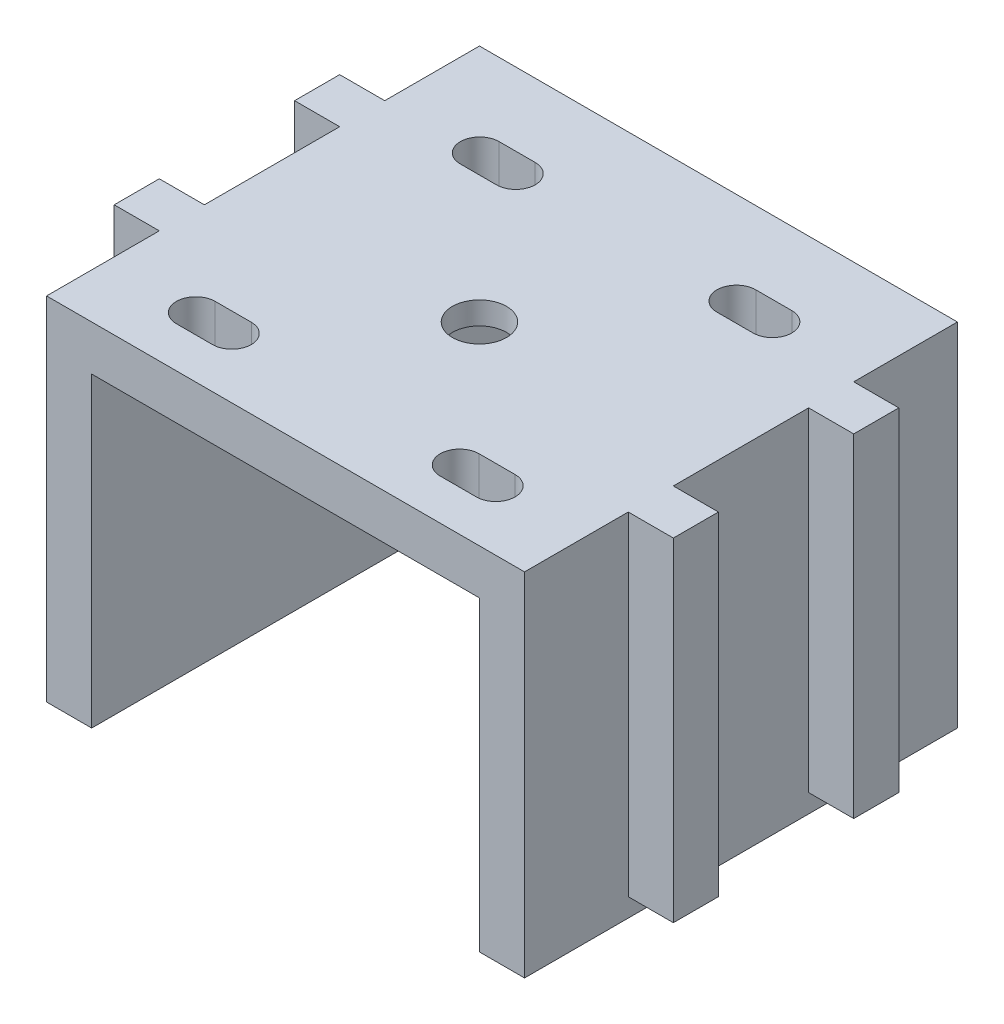
SolidWorks part; units mm, degrees
ref_plane "Front Plane" through (0, 0, 0) normal (1, 0, 0) x (0, 1, 0)
ref_plane "Top Plane" through (0, 0, 0) normal (0, 0, 1) x (0, 1, 0)
ref_plane "Right Plane" through (0, 0, 0) normal (0, 1, 0) x (-1, 0, 0)
sketch "Sketch1" plane through (0, 0, 0) normal (0, 0, 1) x (0, 1, 0)
  line L0 (3.6144, 8.8715) -> (-15.8856, 8.8715)
  line L2 (3.6144, 8.8715) -> (3.6144, -34.1285)
  line L5 (-15.8856, 8.8715) -> (-15.8856, 13.8715)
  line L6 (-15.8856, 13.8715) -> (23.1144, 13.8715)
  line L7 (23.1144, 13.8715) -> (23.1144, -39.1285)
  line L8 (23.1144, -39.1285) -> (-15.8856, -39.1285)
  line L9 (-15.8856, -39.1285) -> (-15.8856, -34.1285)
  line L10 (-15.8856, -34.1285) -> (3.6144, -34.1285)
  dimension "D1" = 39
  dimension "D3" = 19.5
  dimension "D5" = 53
  dimension "D6" = 5
extrude "Boss-Extrude4" add sketch "Sketch1" along normal blind 48
sketch "Sketch2" plane through (0, 0, 48) normal (0, 0, 1) x (1, 0, 0)
  line L0 (39.1285, 23.1144) -> (-13.8715, 23.1144) construction
  line L1 (-8.8715, 18.1144) -> (34.1285, 18.1144)
  line L2 (-8.8715, 18.1144) -> (-8.8715, -24.8856)
  line L3 (-8.8715, -24.8856) -> (34.1285, -24.8856)
  line L4 (34.1285, 18.1144) -> (34.1285, -24.8856)
  line L5 (-13.8715, 23.1144) -> (-13.8715, -15.8856) construction
  dimension "D1" = 43
  dimension "D2" = 43
  dimension "D3" = 5
  dimension "D4" = 5
extrude "Cut-Extrude2" cut sketch "Sketch2" against normal blind 43 contours L2 L3 L4 L1
sketch "Sketch5" plane through (0, 18.1144, 0) normal (0, -1, 0) x (1, 0, 0)
  line L0 (34.1285, 5) -> (34.1285, 48) construction
  line L1 (-8.8715, 5) -> (34.1285, 5) construction
  circle A0 centre (12.6285, 26.5) radius 11.15
  dimension "D1" = 22.3
  dimension "D2" = 21.5
  dimension "D3" = 21.5
extrude "Cut-Extrude3" cut sketch "Sketch5" against normal blind 2.5
sketch "Sketch7" plane through (0, 20.6144, 0) normal (0, -1, 0) x (1, 0, 0)
  circle A0 centre (12.6285, 26.5) radius 3
  circle A1 centre (12.6285, 26.5) radius 11.15 construction
  circle A2 centre (12.6285, 26.5) radius 11.15 construction
  dimension "D1" = 6
  dimension "D2" = 0
  dimension "D3" = 0
extrude "Cut-Extrude4" cut sketch "Sketch7" against normal blind 2.5
sketch "Sketch8" plane through (0, 18.1144, 0) normal (0, -1, 0) x (1, 0, 0)
  line L0 (-4, 41.3244) -> (0, 41.3244) construction
  line L1 (-4, 43.4744) -> (0, 43.4744)
  line L2 (-4, 39.1744) -> (0, 39.1744)
  line L3 (-3.5994, 10.2404) -> (0.4006, 10.2404) construction
  line L4 (28.8564, 10.2404) -> (24.8564, 10.2404) construction
  line L5 (28.8564, 12.3904) -> (24.8564, 12.3904)
  line L6 (12.6285, 48) -> (12.6285, 0) construction
  line L7 (-8.8715, 48) -> (34.1285, 48) construction
  line L8 (-8.8715, 0) -> (34.1285, 0) construction
  line L9 (29.2571, 41.3244) -> (25.2571, 41.3244) construction
  line L10 (29.2571, 43.4744) -> (25.2571, 43.4744)
  line L11 (29.2571, 39.1744) -> (25.2571, 39.1744)
  line L12 (28.8564, 8.0904) -> (24.8564, 8.0904)
  line L13 (-3.5994, 12.3904) -> (0.4006, 12.3904)
  line L14 (-3.5994, 8.0904) -> (0.4006, 8.0904)
  arc A4 (-4, 43.4744) -> (-4, 39.1744) centre (-4, 41.3244) ccw
  arc A5 (0, 39.1744) -> (0, 43.4744) centre (0, 41.3244) ccw
  arc A6 (29.2571, 43.4744) -> (29.2571, 39.1744) centre (29.2571, 41.3244) cw
  arc A7 (25.2571, 39.1744) -> (25.2571, 43.4744) centre (25.2571, 41.3244) cw
  arc A8 (-3.5994, 12.3904) -> (-3.5994, 8.0904) centre (-3.5994, 10.2404) ccw
  arc A9 (0.4006, 8.0904) -> (0.4006, 12.3904) centre (0.4006, 10.2404) ccw
  arc A10 (28.8564, 12.3904) -> (28.8564, 8.0904) centre (28.8564, 10.2404) cw
  arc A11 (24.8564, 8.0904) -> (24.8564, 12.3904) centre (24.8564, 10.2404) cw
  point P8 (-2, 41.3244)
  point P14 (26.8564, 10.2404)
  point P15 (-1.5994, 10.2404)
  point P27 (27.2571, 41.3244)
  dimension "D5" = 4
  dimension "D4" = 2.15
extrude "Cut-Extrude5" cut sketch "Sketch8" against normal blind 5
sketch "Sketch9" plane through (-13.8715, 0, 0) normal (-1, 0, 0) x (0, -1, 0)
  line L0 (-23.1144, 48) -> (-23.1144, 0) construction
  line L1 (-23.1144, 35.5) -> (13.8277, 35.5)
  line L2 (-23.1144, 35.5) -> (-23.1144, 30.5)
  line L3 (-23.1144, 30.5) -> (13.8277, 30.5)
  line L4 (13.8277, 35.5) -> (13.8277, 30.5)
  line L6 (-23.1144, 15.5) -> (13.8277, 15.5)
  line L7 (-23.1144, 15.5) -> (-23.1144, 10.5)
  line L8 (-23.1144, 10.5) -> (13.8277, 10.5)
  line L9 (13.8277, 15.5) -> (13.8277, 10.5)
  line L11 (-23.1144, 0) -> (15.8856, 0) construction
  line M10 (15.8856, 0) -> (15.8856, 48)
  line M12 (-23.1144, 48) -> (-23.1144, 0)
  dimension "D1" = 5
  dimension "D2" = 5
  dimension "D3" = 15
  dimension "D4" = 10.5
extrude "Boss-Extrude5" add sketch "Sketch9" along normal blind 5 contours L8 L6 M12 M10 | L1 L4 L3 L2
sketch "Sketch12" plane through (39.1285, 0, 0) normal (1, 0, 0) x (0, 1, 0)
  line L0 (23.1144, 48) -> (23.1144, 0) construction
  line L1 (-13.8277, 36.5) -> (23.1144, 36.5)
  line L2 (-13.8277, 36.5) -> (-13.8277, 31.5)
  line L3 (-13.8277, 31.5) -> (23.1144, 31.5)
  line L4 (23.1144, 36.5) -> (23.1144, 31.5)
  line L5 (-13.8277, 16.5) -> (23.1144, 16.5)
  line L6 (-13.8277, 16.5) -> (-13.8277, 11.5)
  line L7 (-13.8277, 11.5) -> (23.1144, 11.5)
  line L8 (23.1144, 16.5) -> (23.1144, 11.5)
  line L13 (-15.8856, 48) -> (23.1144, 48) construction
  dimension "D1" = 5
  dimension "D2" = 5
  dimension "D3" = 15
  dimension "D4" = 11.5
extrude "Boss-Extrude6" add sketch "Sketch12" along normal blind 5
